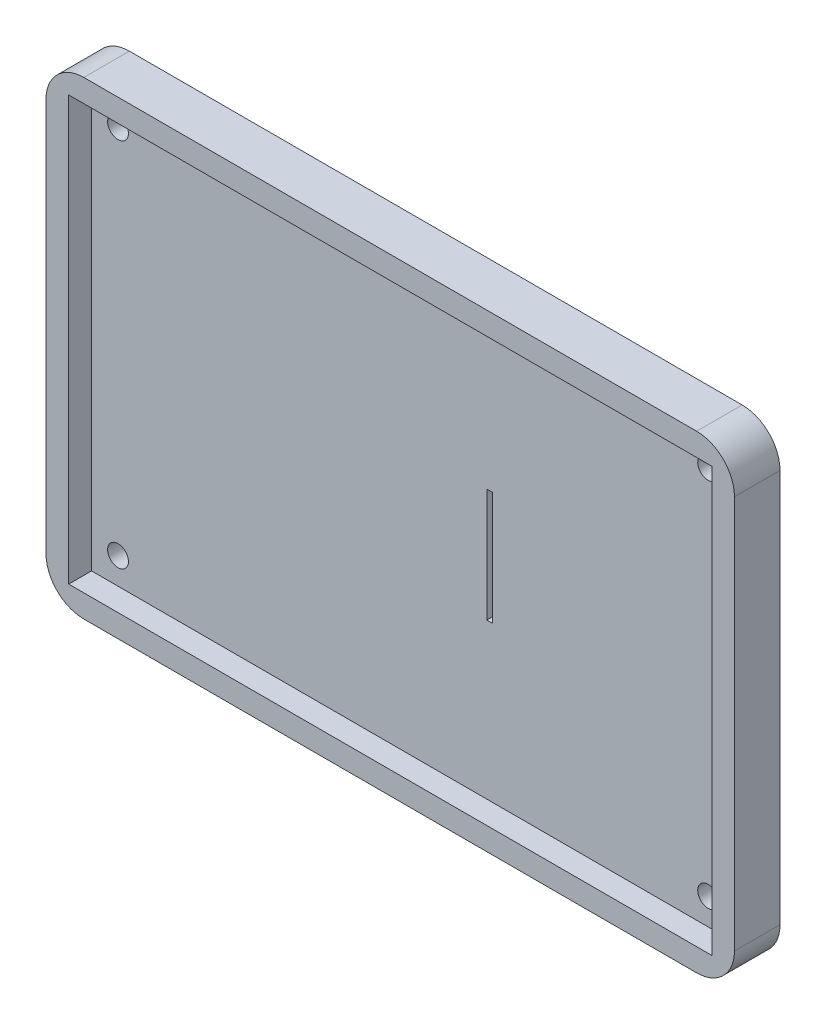
SolidWorks part; units mm, degrees
ref_plane "Front Plane" through (0, 0, 0) normal (0, 0, 1) x (1, 0, 0)
ref_plane "Top Plane" through (0, 0, 0) normal (0, 1, 0) x (1, 0, 0)
ref_plane "Right Plane" through (0, 0, 0) normal (1, 0, 0) x (0, 0, -1)
sketch "Sketch1" plane through (0, 0, 0) normal (0, 0, 1) x (1, 0, 0)
  line L0 (-85.568, 0) -> (114.4621, 0) construction
  line L1 (-45.5, -31) -> (45.5, -31)
  line L2 (-45.5, -31) -> (-45.5, 31)
  line L3 (-45.5, 31) -> (45.5, 31)
  line L4 (45.5, -31) -> (45.5, 31)
  line L5 (-45.5, -31) -> (45.5, 31) construction
  line L6 (-45.5, 31) -> (45.5, -31) construction
  line L7 (0, 61.7999) -> (0, -59.1102) construction
  line L13 (-42.5, -28.956) -> (42.5, 28.956) construction
  line L14 (-42.5, 28.956) -> (42.5, -28.956) construction
  circle A0 centre (-39, 24.5) radius 1.375
  circle A4 centre (-39, -24.5) radius 1.375
  circle A5 centre (39, -24.5) radius 1.375
  circle A6 centre (39, 24.5) radius 1.375
  point P0 (0, 0)
  point P12 (0, 0)
  dimension "D3" = 2.75
  dimension "D4" = 57.9121
  dimension "D5" = 85
  dimension "D1" = 91
  dimension "D2" = 62
  dimension "D7" = 6.5
  dimension "D8" = 6.5
extrude "Boss-Extrude1" add sketch "Sketch1" along normal blind 3
sketch "Sketch2" plane through (0, 0, 3) normal (0, 0, 1) x (1, 0, 0)
  line L1 (-42.5, -28) -> (42.5, -28)
  line L2 (-42.5, -28) -> (-42.5, 28)
  line L3 (-42.5, 28) -> (42.5, 28)
  line L4 (42.5, -28) -> (42.5, 28)
  line L5 (-42.5, -28) -> (42.5, 28) construction
  line L6 (-42.5, 28) -> (42.5, -28) construction
  line L7 (-45.5, -31) -> (45.5, -31)
  line L8 (-45.5, -31) -> (-45.5, 31)
  line L9 (-45.5, 31) -> (45.5, 31)
  line L10 (45.5, -31) -> (45.5, 31)
  line L11 (-45.5, -31) -> (45.5, 31) construction
  line L12 (-45.5, 31) -> (45.5, -31) construction
  point P0 (0, 0)
  point P5 (0, 0)
  dimension "D1" = 56
  dimension "D2" = 85
extrude "Boss-Extrude2" add sketch "Sketch2" along normal blind 3.02
fillet "Fillet1" radius 5 4 edges at (-45.5, -31, 3.01) (45.5, 31, 3.01) (45.5, -31, 3.01) (-45.5, 31, 3.01)
sketch "Sketch3" plane through (0, 0, 0) normal (0, 0, -1) x (-1, 0, 0)
  line L0 (-45.5, -26) -> (-45.5, 26) construction
  line L1 (-10.5, 7.5) -> (-9.75, 7.5)
  line L2 (-10.5, 7.5) -> (-10.5, -7.5)
  line L3 (-10.5, -7.5) -> (-9.75, -7.5)
  line L4 (-9.75, 7.5) -> (-9.75, -7.5)
  line L5 (-72.9234, 0) -> (76.901, 0) construction
  point P9 (-9.75, 0)
  dimension "D1" = 15
  dimension "D2" = 0.75
  dimension "D3" = 35
extrude "Cut-Extrude1" cut sketch "Sketch3" along direction (0, 0, -1) on the side against the normal up to surface (3 mm away)
